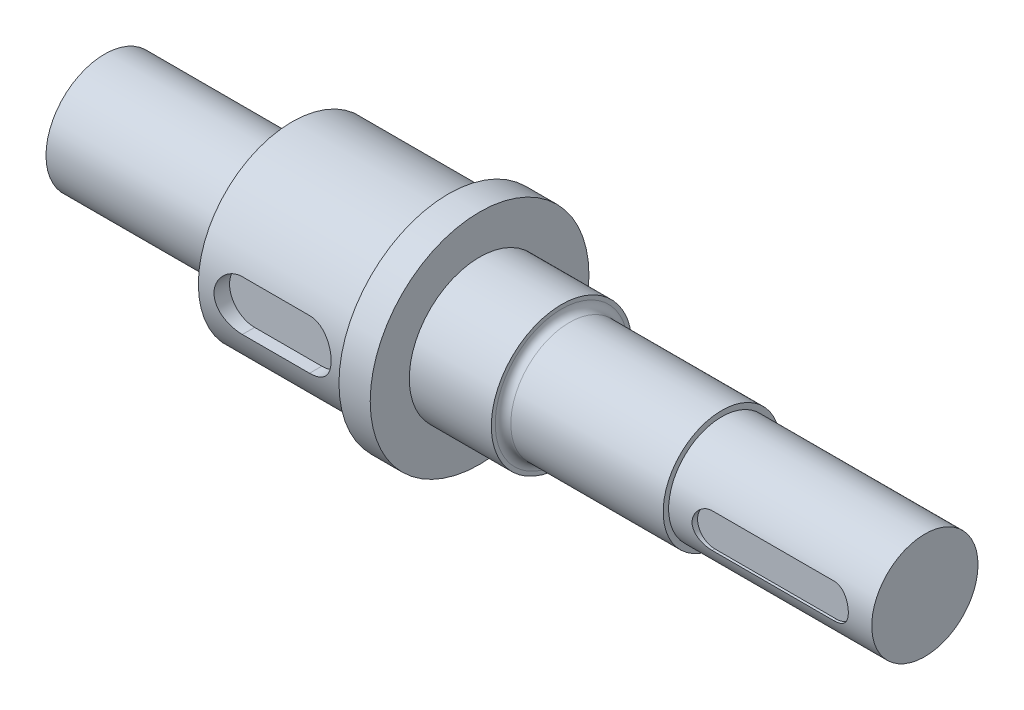
SolidWorks part; units mm, degrees
ref_plane "前视基准面" through (0, 0, 0) normal (0, 0, 1) x (1, 0, 0)
ref_plane "上视基准面" through (0, 0, 0) normal (0, 1, 0) x (1, 0, 0)
ref_plane "右视基准面" through (0, 0, 0) normal (1, 0, 0) x (0, 0, -1)
sketch "草图1" plane through (0, 0, 0) normal (1, 0, 0) x (0, 0, -1)
  circle A0 centre (0, 0) radius 70
  dimension "D1" = 140
extrude "拉伸1" add sketch "草图1" along normal blind 525
sketch "草图2" plane through (525, 0, 0) normal (1, 0, 0) x (0, 0, -1)
  circle A0 centre (0, 0) radius 45
  dimension "D1" = 90
extrude "拉伸2" cut sketch "草图2" against normal blind 285 flip side to cut
sketch "草图3" plane through (240, 0, 0) normal (1, 0, 0) x (0, 0, -1)
  circle A1 centre (0, 0) radius 60
  dimension "D1" = 120
extrude "拉伸3" cut sketch "草图3" against normal through all from offset 20 flip side to cut offset against normal yes
sketch "草图4" plane through (525, 0, 0) normal (1, 0, 0) x (0, 0, -1)
  circle A0 centre (0, 0) radius 37.5
  dimension "D1" = 75
extrude "拉伸4" cut sketch "草图4" against normal offset from surface (232.5 mm away) 52.5 flip side to cut up to face at (240, 0, -45)
sketch "草图5" plane through (0, 0, 0) normal (-1, 0, 0) x (0, 0, 1)
  circle A0 centre (0, 0) radius 37.5 construction
  circle A2 centre (0, 0) radius 37.5
extrude "拉伸5" cut sketch "草图5" against normal offset from surface (120 mm away) 100 flip side to cut up to face at (220, 0, -60)
sketch "草图6" plane through (0, 0, 0) normal (0, 0, 1) x (1, 0, 0)
  line L0 (146, 0) -> (189, 0) construction
  line L1 (146, 16) -> (189, 16)
  line L2 (146, -16) -> (189, -16)
  line L3 (220, 60) -> (220, -60) construction
  arc A0 (146, 16) -> (146, -16) centre (146, 0) ccw
  arc A1 (189, -16) -> (189, 16) centre (189, 0) ccw
  point P3 (167.5, 0)
  dimension "D1" = 75
  dimension "D2" = 15
  dimension "D3" = 32
extrude "拉伸6" cut sketch "草图6" along normal through all from offset 50
sketch "草图8" plane through (525, 0, 0) normal (1, 0, 0) x (0, 0, -1)
  circle A0 centre (0, 0) radius 34
  dimension "D1" = 68
extrude "切除-拉伸1" cut sketch "草图8" against normal blind 130 flip side to cut
sketch "草图7" plane through (0, 0, 0) normal (0, 0, 1) x (1, 0, 0)
  line L0 (421, 0) -> (499, 0) construction
  line L1 (421, 11) -> (499, 11)
  line L2 (421, -11) -> (499, -11)
  line L3 (525, -37.5) -> (525, 37.5) construction
  arc A0 (421, 11) -> (421, -11) centre (421, 0) ccw
  arc A1 (499, -11) -> (499, 11) centre (499, 0) ccw
  point P3 (460, 0)
  dimension "D1" = 100
  dimension "D2" = 15
  dimension "D3" = 22
extrude "拉伸7" cut sketch "草图7" along normal through all from offset 30.5
fillet "圆角1" radius 5 2 edges at (292.5, 0, -37.5) (120, 0, -37.5)
